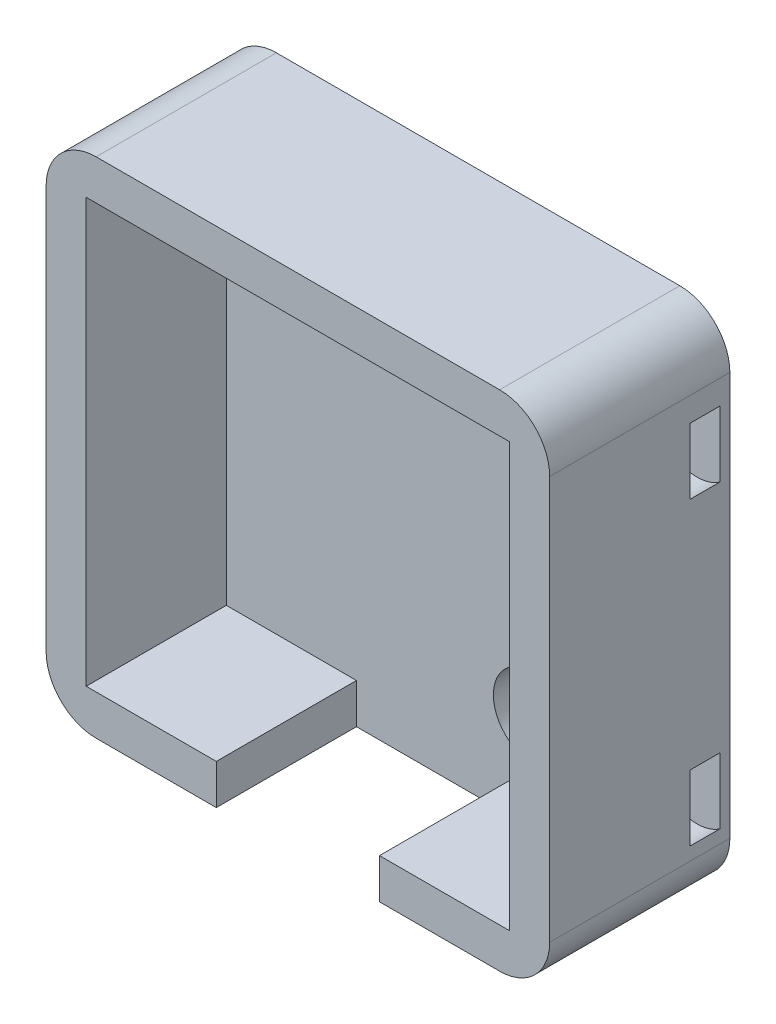
SolidWorks part; units mm, degrees
ref_plane "Front" through (0, 0, 0) normal (0, 0, 1) x (1, 0, 0)
ref_plane "Top" through (0, 0, 0) normal (0, 1, 0) x (1, 0, 0)
ref_plane "Right" through (0, 0, 0) normal (1, 0, 0) x (0, 0, -1)
sketch "Esquisse1" plane through (0, 0, 0) normal (0, 0, 1) x (1, 0, 0)
  line L1 (0, 0) -> (50.3, 0)
  line L2 (0, 0) -> (0, 50.3)
  line L3 (0, 50.3) -> (50.3, 50.3)
  line L4 (50.3, 0) -> (50.3, 50.3)
  dimension "D1" = 50.3
  dimension "D2" = 50.3
extrude "Boss.-Extru.1" add sketch "Esquisse1" along normal blind 4
sketch "Esquisse2" plane through (0, 0, 4) normal (0, 0, 1) x (1, 0, 0)
  line L0 (50.3, 50.3) -> (0, 50.3) construction
  line L1 (4, 46.3) -> (46.3, 46.3)
  line L2 (4, 46.3) -> (4, 4)
  line L3 (4, 4) -> (17, 4)
  line L4 (46.3, 46.3) -> (46.3, 4)
  line L5 (0, 0) -> (50.3, 0) construction
  line L6 (0, 50.3) -> (0, 0) construction
  line L7 (50.3, 0) -> (50.3, 50.3) construction
  line L8 (33.3, 4) -> (46.3, 4)
  line L9 (33.3, 0) -> (50.3, 0)
  line L10 (17, 4) -> (17, 0)
  line L11 (0, 50.3) -> (50.3, 50.3)
  line L12 (33.3, 4) -> (33.3, 0)
  line L13 (0, 50.3) -> (0, 0)
  line L14 (0, 0) -> (17, 0)
  line L15 (50.3, 50.3) -> (50.3, 0)
  point P16 (17, 2)
  point P17 (33.3, 2)
  dimension "D1" = 4
  dimension "D2" = 4
  dimension "D3" = 4
  dimension "D4" = 4
  dimension "D5" = 16.3
  dimension "D6" = 13
extrude "Boss.-Extru.2" add sketch "Esquisse2" along normal blind 14
sketch "Esquisse3" plane through (0, 0, 0) normal (0, 0, -1) x (-1, 0, 0)
  circle A0 centre (-34.6751, 39.6) radius 1.5
  circle A1 centre (-59.6751, 39.6) radius 1.5
  circle A2 centre (-59.6751, 9.6) radius 1.5
  circle A3 centre (-34.6751, 9.6) radius 1.5
  dimension "D1" = 3
  dimension "D2" = 3
  dimension "D3" = 3
  dimension "D4" = 3
extrude "Enlèv. mat.-Extru.1" cut sketch "Esquisse3" against normal through all
fillet "Congé2" radius 5 1 edges at (0, 50.3, 9)
sketch "Esquisse4" plane through (0, 0, 4) normal (0, 0, 1) x (1, 0, 0)
  circle A0 centre (34.6751, 39.6) radius 4
  circle A1 centre (34.6751, 9.6) radius 4
  circle A2 centre (48.0242, 39.6) radius 4
  circle A3 centre (48.0242, 9.6) radius 4
  dimension "D1" = 8
  dimension "D2" = 8
  dimension "D3" = 8
  dimension "D4" = 8
extrude "Enlèv. mat.-Extru.2" cut sketch "Esquisse4" against normal blind 3
fillet "Congé6" radius 5 3 edges at (50.3, 50.3, 9) (0, 0, 9) (50.3, 0, 9)
